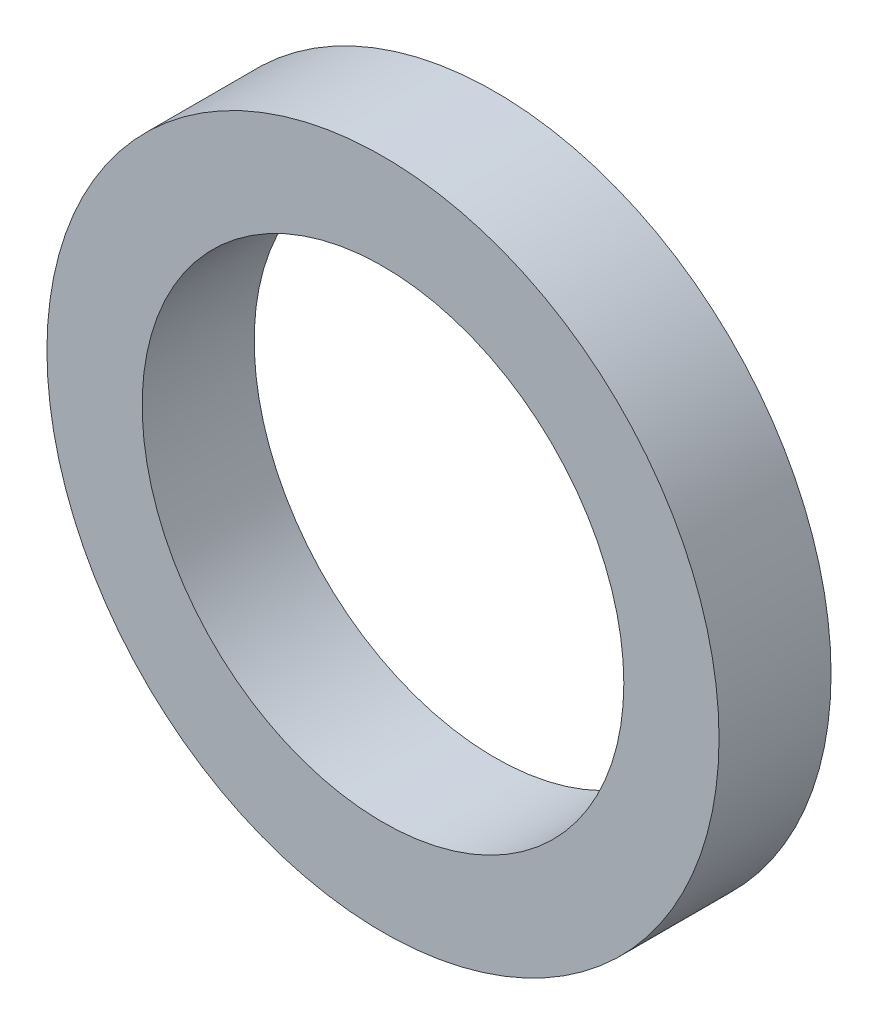
SolidWorks part; units mm, degrees
material "1.4310 (X10CrNi18-8)"
ref_plane "Front Plane" through (0, 0, 0) normal (0, 0, 1) x (1, 0, 0)
ref_plane "Top Plane" through (0, 0, 0) normal (0, 1, 0) x (1, 0, 0)
ref_plane "Right Plane" through (0, 0, 0) normal (1, 0, 0) x (0, 0, -1)
sketch "Sketch1" plane through (0, 0, 0) normal (1, 0, 0) x (0, 0, -1)
  line L2 (0.5, -3) -> (-0.5, -3) construction
  line L3 (0.5, -3) -> (0.5, 3) construction
  line L4 (0.5, 3) -> (-0.5, 3) construction
  line L5 (-0.5, -3) -> (-0.5, 3) construction
  line L6 (0.5, -3) -> (-0.5, 3) construction
  line L7 (0.5, 3) -> (-0.5, -3) construction
  point P0 (0, 0)
  point P4 (0, 0)
  dimension "Length" = 1
  dimension "OD" = 6
sketch "Sketch2" plane through (0, 0, 0) normal (0, 0, 1) x (1, 0, 0)
  line L0 (0, -2.15) -> (0, 2.15) construction
  point P4 (0, 0)
  dimension "ID" = 4.3
sketch "Sketch3" plane through (0, 0, 0) normal (0, 0, 1) x (1, 0, 0)
  line L0 (0, -3) -> (0, 3) construction
  circle A0 centre (0, 0) radius 2.15
  circle A1 centre (0, 0) radius 3
  dimension "D1" = 6
extrude "Boss-Extrude1" add sketch "Sketch3" against normal up to vertex (0.5 mm away) and the other way up to vertex (0.5 mm away) up to point (0, 3, -0.5) other way up to point (0, 3, 0.5)
equation "\"D1@Sketch3\"=\"OD@Sketch1\""
